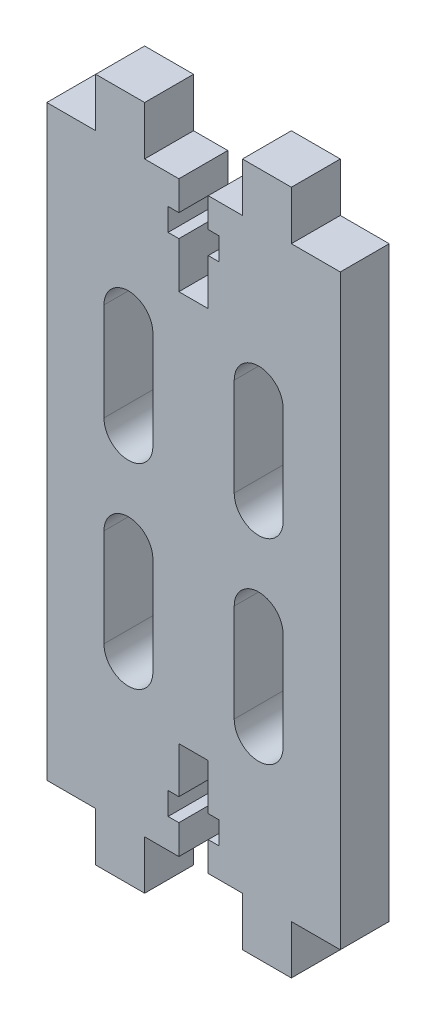
SolidWorks part; units mm, degrees
ref_plane "Front Plane" through (0, 0, 0) normal (0, 0, 1) x (1, 0, 0)
ref_plane "Top Plane" through (0, 0, 0) normal (0, 1, 0) x (1, 0, 0)
ref_plane "Right Plane" through (0, 0, 0) normal (1, 0, 0) x (0, 0, -1)
sketch "Sketch1" plane through (0, 0, 0) normal (0, 0, 1) x (1, 0, 0)
  line L0 (0, 72.0719) -> (0, -22.2682) construction
  line L1 (-15, 30) -> (-15, -30)
  line L2 (15, 30) -> (15, -30)
  line L3 (0, 0) -> (45.6439, 0) construction
  line L4 (-15, 30) -> (15, 30)
  line L5 (-15, -30) -> (15, -30)
  line L6 (-6.6565, -15) -> (-6.6565, -5) construction
  line L7 (-9.1565, -15) -> (-9.1565, -5)
  line L8 (-4.1565, -15) -> (-4.1565, -5)
  line L9 (6.6565, -15) -> (6.6565, -5) construction
  line L10 (9.1565, -15) -> (9.1565, -5)
  line L11 (4.1565, -15) -> (4.1565, -5)
  line L12 (6.6565, 15) -> (6.6565, 5) construction
  line L13 (9.1565, 15) -> (9.1565, 5)
  line L14 (4.1565, 15) -> (4.1565, 5)
  line L15 (-6.6565, 15) -> (-6.6565, 5) construction
  line L16 (-9.1565, 15) -> (-9.1565, 5)
  line L17 (-4.1565, 15) -> (-4.1565, 5)
  arc A0 (-9.1565, -15) -> (-4.1565, -15) centre (-6.6565, -15) ccw
  arc A1 (-4.1565, -5) -> (-9.1565, -5) centre (-6.6565, -5) ccw
  arc A2 (9.1565, -15) -> (4.1565, -15) centre (6.6565, -15) cw
  arc A3 (4.1565, -5) -> (9.1565, -5) centre (6.6565, -5) cw
  arc A4 (9.1565, 15) -> (4.1565, 15) centre (6.6565, 15) ccw
  arc A5 (4.1565, 5) -> (9.1565, 5) centre (6.6565, 5) ccw
  arc A6 (-9.1565, 15) -> (-4.1565, 15) centre (-6.6565, 15) cw
  arc A7 (-4.1565, 5) -> (-9.1565, 5) centre (-6.6565, 5) cw
  point P11 (-6.6565, -10)
  point P16 (0, 0)
  point P17 (0, 0)
  point P18 (0, 0)
  point P19 (0, 0)
  point P22 (6.6565, -10)
  point P29 (6.6565, 10)
  point P36 (-6.6565, 10)
  line B0 (-2.6, -27) -> (-2.6, -24.7)
  line B1 (1.5, -24.7) -> (1.5, -20)
  line B2 (-1.5, -20) -> (-1.5, -24.7)
  line B3 (-2.6, -24.7) -> (-1.5, -24.7)
  line B4 (0, -30) -> (0, -18.7792) construction
  line B5 (-1.5, -30) -> (-5, -30)
  line B6 (-5, -35) -> (-10, -35)
  line B7 (-10, -35) -> (-10, -30)
  line B8 (-5, -35) -> (-5, -30)
  line B9 (1.5, -30) -> (5, -30)
  line B10 (5, -30) -> (5, -35)
  line B11 (5, -35) -> (10, -35)
  line B12 (10, -35) -> (10, -30)
  line B13 (1.5, -30) -> (1.5, -27)
  line B14 (0, -20) -> (0, -30) construction
  line B15 (-1.5, -27) -> (-1.5, -30)
  line B16 (2.6, -24.7) -> (2.6, -27)
  line B17 (-1.5, -30) -> (1.5, -30) construction
  line B18 (1.5, -24.7) -> (2.6, -24.7)
  line B19 (2.6, -27) -> (1.5, -27)
  line B20 (1.5, -20) -> (-1.5, -20)
  line B21 (-1.5, -27) -> (-2.6, -27)
  line B22 (2.6, 27) -> (2.6, 24.7)
  line B23 (-1.5, 24.7) -> (-1.5, 20)
  line B24 (1.5, 20) -> (1.5, 24.7)
  line B25 (2.6, 24.7) -> (1.5, 24.7)
  line B26 (0, 30) -> (0, 18.7792) construction
  line B27 (1.5, 30) -> (5, 30)
  line B28 (5, 35) -> (10, 35)
  line B29 (10, 35) -> (10, 30)
  line B30 (5, 35) -> (5, 30)
  line B31 (-1.5, 30) -> (-5, 30)
  line B32 (-5, 30) -> (-5, 35)
  line B33 (-5, 35) -> (-10, 35)
  line B34 (-10, 35) -> (-10, 30)
  line B35 (-1.5, 30) -> (-1.5, 27)
  line B36 (0, 20) -> (0, 30) construction
  line B37 (1.5, 27) -> (1.5, 30)
  line B38 (-2.6, 24.7) -> (-2.6, 27)
  line B39 (1.5, 30) -> (-1.5, 30) construction
  line B40 (-1.5, 24.7) -> (-2.6, 24.7)
  line B41 (-2.6, 27) -> (-1.5, 27)
  line B42 (-1.5, 20) -> (1.5, 20)
  line B43 (1.5, 27) -> (2.6, 27)
  dimension "D1" = 60
  dimension "D2" = 5
  dimension "D3" = 30
  dimension "D4" = 10
  dimension "D5" = 20
sketch_block_instance "Insert M3 plots ep 5mm-1"
sketch_block "Insert M3 plots ep 5mm" parameters "D1"=10, "D2"=5, "D3"=5
sketch_block_instance "Decoupe Insert M3-4"
sketch_block "Decoupe Insert M3" parameters "D1"=5.2, "D2"=3, "D3"=2.3, "D4"=3, "D5"=10
sketch_block_instance "Insert M3 plots ep 5mm-2"
extrude "Boss-Extrude1" add sketch "Sketch1" along normal blind 5 contours B28 B30 L4 B29 | B37 B43 B22 B25 B24 B42 B23 B40 B38 B41 B35 L4 L1 L5 B15 B21 B0 B3 B2 B20 B1 B18 B16 B19 B13 L2 | B33 B34 L4 B32 | B6 B8 L5 B7 | B11 B12 L5 B10
